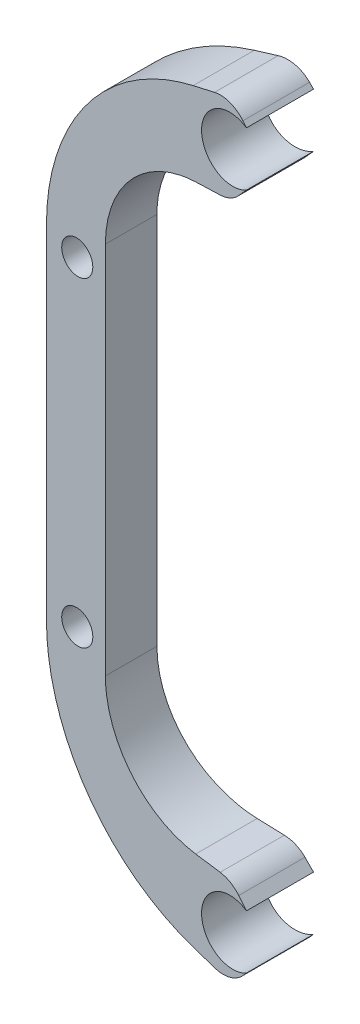
SolidWorks part; units mm, degrees
ref_plane "前视基准面" through (0, 0, 0) normal (0, 0, 1) x (1, 0, 0)
ref_plane "上视基准面" through (0, 0, 0) normal (0, 1, 0) x (1, 0, 0)
ref_plane "右视基准面" through (0, 0, 0) normal (1, 0, 0) x (0, 0, -1)
sketch "草图1" plane through (0, 0, 0) normal (0, 0, 1) x (1, 0, 0)
  line L0 (6.0175, 13.1888) -> (6.0175, -28.6712) construction
  line L1 (13.5175, 19.7888) -> (-1.4825, 19.7888) construction
  line L2 (13.5175, 19.7888) -> (13.5175, 13.7888) construction
  line L3 (13.5175, 13.7888) -> (-1.4825, 13.7888) construction
  line L10 (13.5175, 19.7888) -> (-1.4825, 13.7888) construction
  line L14 (13.5175, 13.7888) -> (-1.4825, 19.7888) construction
  line L15 (13.5175, -25.6712) -> (-1.4825, -25.6712) construction
  line L20 (13.5175, -25.6712) -> (13.5175, -31.6712) construction
  line L21 (13.5175, -31.6712) -> (-1.4825, -31.6712) construction
  line L22 (-1.4825, -25.6712) -> (-1.4825, -31.6712) construction
  line L24 (13.5175, -25.6712) -> (-1.4825, -31.6712) construction
  line L25 (13.5175, -31.6712) -> (-1.4825, -25.6712) construction
  line L26 (-1.4825, 13.7888) -> (-1.4825, 19.7888) construction
  line L27 (6.0175, 19.7888) -> (-7.0575, 16.2854)
  line L28 (-7.0575, 16.2854) -> (-7.0575, -16.1396)
  line L32 (6.0175, -25.6712) -> (-2.8875, -24.8921)
  line L34 (-2.8875, -24.8921) -> (-2.8875, 13.0097)
  line L35 (-2.8875, 13.0097) -> (6.0175, 13.7888)
  line L37 (7.0894, 18.1222) -> (7.0894, 15.0061) construction
  line L38 (6.0175, 13.7888) -> (7.0894, 14.983)
  line L40 (6.0175, 19.7888) -> (7.0894, 18.5946)
  line L42 (6.0175, -25.6712) -> (7.0894, -26.8654)
  line L45 (7.0894, -30.477) -> (6.0175, -31.6712)
  line L46 (6.0175, -31.6712) -> (-7.0575, -28.1677)
  line L47 (-7.0575, -28.1677) -> (-7.0575, -16.1396)
  line L48 (-4.8792, 4.7888) -> (-4.8792, -16.6712) construction
  circle A6 centre (6.0175, 16.7888) radius 2.1 construction
  circle A7 centre (6.0175, -28.6712) radius 2.1 construction
  arc A8 (7.0894, -26.8654) -> (7.0894, -30.477) centre (6.0175, -28.6712) ccw
  arc A9 (7.0894, 14.983) -> (7.0894, 18.5946) centre (6.0175, 16.7888) cw
  circle A10 centre (-4.8792, 4.7888) radius 1.1
  circle A11 centre (-4.8792, -16.6712) radius 1.1
  dimension "D1" = 45.46
  dimension "D2" = 6
  dimension "D10" = 12
  dimension "D3" = 6
  dimension "D4" = 15
  dimension "D5" = 15
  dimension "D6" = 85
  dimension "D7" = 85
  dimension "D8" = 105
  dimension "D9" = 105
  dimension "D11" = 12
extrude "凸台-拉伸2" add sketch "草图1" along normal blind 4.5
fillet "圆角1" radius 7 2 edges at (-2.8875, 13.0097, 2.25) (-2.8875, -24.8921, 2.25)
fillet "圆角2" radius 14 2 edges at (-7.0575, 16.2854, 2.25) (-7.0575, -28.1677, 2.25)
fillet "圆角3" radius 2 4 edges at (6.0175, 19.7888, 2.25) (6.0175, 13.7888, 2.25) (6.0175, -31.6712, 2.25) (6.0175, -25.6712, 2.25)
sketch "草图2" plane through (0, 0, 0) normal (0, 1, 0) x (1, 0, 0)
  line L0 (7.0894, 0) -> (-9.9377, -0.8924) construction
  line L1 (-9.9377, -0.8924) -> (-9.6534, 2.8887)
  line L2 (-9.6534, 2.8887) -> (6.0918, 2.8887)
  line L3 (6.0918, 2.8887) -> (7.0894, 0)
  line L4 (7.0894, -4.5) -> (-9.9279, -3.6082)
  line L5 (-9.9279, -3.6082) -> (-9.6673, -5.6136)
  line L6 (-9.6673, -5.6136) -> (7.0894, -5.4075)
  line L7 (7.0894, -5.4075) -> (7.0894, -4.5)
  line L9 (-7.0575, -4.5) -> (3.319, -4.5) construction
  line L10 (3.319, 0) -> (-7.0575, 0) construction
  line L11 (7.0894, 0) -> (-4.9288, -0.6298)
  line L12 (-4.9288, -0.6298) -> (-9.5046, -0.6298)
  line L13 (-9.5046, -0.6298) -> (-9.9377, -0.8924)
  point P16 (-4.9288, -0.6298)
  dimension "D1" = 3
  dimension "D2" = 3
extrude "切除-拉伸1" cut sketch "草图2" against normal through all both and the other way through all
